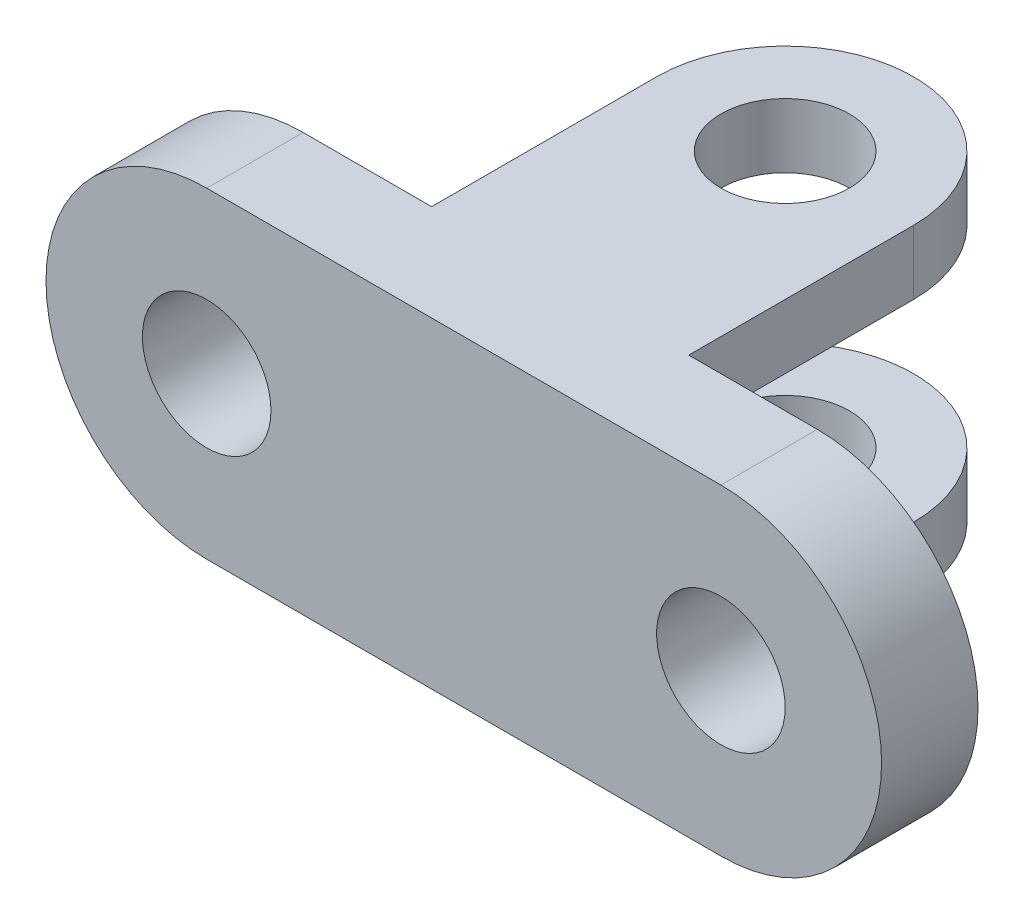
SolidWorks part; units mm, degrees
ref_plane "Front Plane" through (0, 0, 0) normal (0, 0, 1) x (1, 0, 0)
ref_plane "Top Plane" through (0, 0, 0) normal (0, 1, 0) x (1, 0, 0)
ref_plane "Right Plane" through (0, 0, 0) normal (1, 0, 0) x (0, 0, -1)
sketch "Sketch7" plane through (0, 0, 0) normal (0, 0, 1) x (1, 0, 0)
  line L0 (-40, 0) -> (40, 0) construction
  line L1 (-40, 25) -> (40, 25)
  line L2 (-40, -25) -> (40, -25)
  arc A0 (-40, 25) -> (-40, -25) centre (-40, 0) ccw
  arc A1 (40, -25) -> (40, 25) centre (40, 0) ccw
  circle A2 centre (-40, 0) radius 10
  circle A3 centre (40, 0) radius 10
  point P3 (0, 0)
  dimension "D1" = 25
  dimension "D3" = 20
  dimension "D2" = 80
extrude "Boss-Extrude2" add sketch "Sketch7" against normal blind 15
sketch "Sketch8" plane through (0, 0, 0) normal (0, 1, 0) x (1, 0, 0)
  line L0 (-20, 15) -> (-20, 50)
  line L1 (40, 15) -> (-40, 15) construction
  line L2 (20, 15) -> (20, 50)
  line L3 (-20, 15) -> (20, 15)
  arc A0 (20, 50) -> (-20, 50) centre (0, 50) ccw
  circle A1 centre (0, 50) radius 10
  dimension "D2" = 20
  dimension "D4" = 20
  dimension "D1" = 35
  dimension "D3" = 20
extrude "Boss-Extrude3" add sketch "Sketch8" along normal through all and the other way through all contours L0 A0 L2 L3
hole_wizard "Ø2.0mm Dowel Hole1" positions "Sketch9" profile "Sketch10" hole size "Ø2.0" standard "ISO"
sketch "Sketch9" plane through (0, -25, 0) normal (0, -1, 0) x (1, 0, 0)
  line L0 (20, -15) -> (40, -15) construction
  point P0 (0, -50)
  dimension "D1" = 35
sketch "Sketch10" plane through (0, -25, -50) normal (1, 0, 0) x (0, 0, -1)
  line L0 (0, 0) -> (0, 100)
  line L1 (0, 100) -> (10, 100)
  line L2 (10, 100) -> (10, 0)
  line L5 (10, 0) -> (0, 0)
  line L10 (0, 100) -> (-10, 100) construction
  line L11 (0, -6.35) -> (0, 107.95) construction
  dimension "Hole Dia." = 20
  dimension "Hole Depth" = 100
  dimension "Drill Angle" = 180
sketch "Sketch12" plane through (0, 0, 0) normal (0, 1, 0) x (1, 0, 0)
  line L0 (-20, 15) -> (-20, 50)
  line L1 (20, 15) -> (20, 50) construction
  line L2 (20, 15) -> (20, 50)
  line L3 (-20, 15) -> (20, 15)
  arc A0 (20, 50) -> (-20, 50) centre (0, 50) ccw construction
  arc A1 (20, 50) -> (-20, 50) centre (0, 50) ccw
  dimension "D1" = 40
extrude "Cut-Extrude1" cut sketch "Sketch12" against normal blind 15 and the other way blind 15
